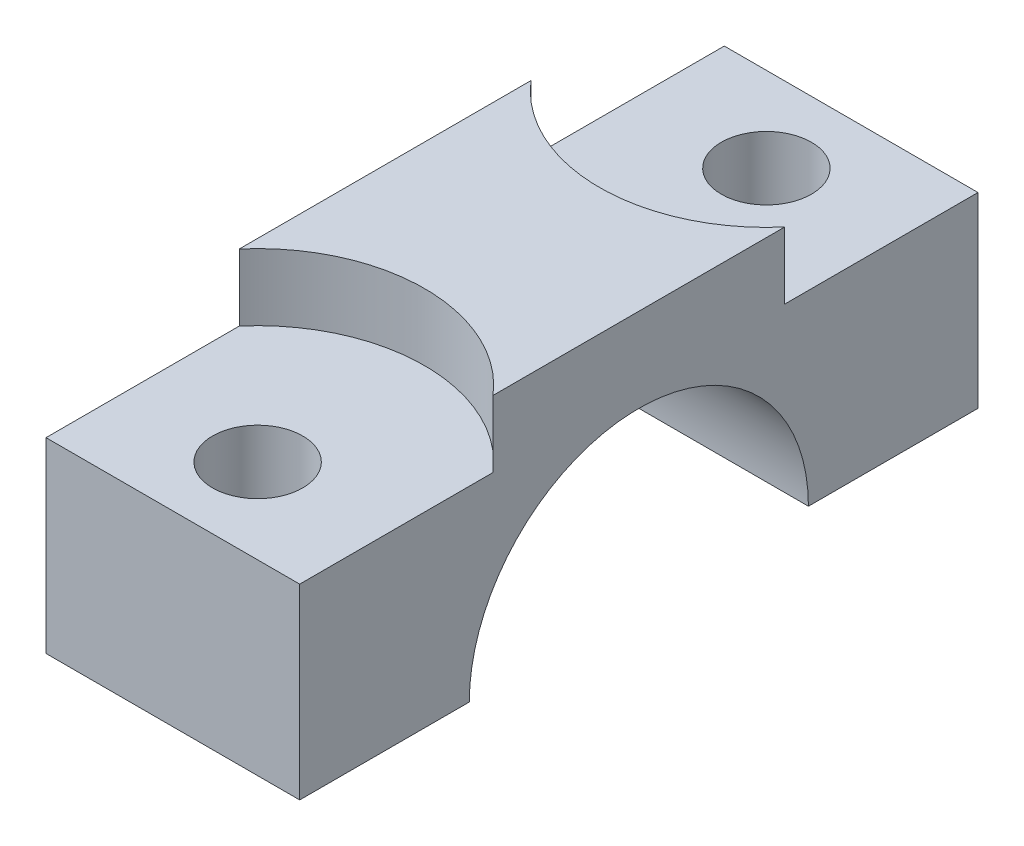
SolidWorks part; units mm, degrees
ref_plane "Front Plane" through (0, 0, 0) normal (0, 0, 1) x (1, 0, 0)
ref_plane "Top Plane" through (0, 0, 0) normal (0, 1, 0) x (1, 0, 0)
ref_plane "Right Plane" through (0, 0, 0) normal (1, 0, 0) x (0, 0, -1)
sketch "Sketch1" plane through (0, 0, 0) normal (1, 0, 0) x (0, 0, -1)
  line L1 (-25.4, 19) -> (25.4, 19)
  line L2 (-25.4, 19) -> (-25.4, 0)
  line L3 (-25.4, 0) -> (25.4, 0)
  line L4 (25.4, 19) -> (25.4, 0)
  circle A0 centre (0, 0) radius 12.7
  dimension "D3" = 25.4
  dimension "D1" = 50.8
  dimension "D2" = 19
extrude "Boss-Extrude1" add sketch "Sketch1" along normal mid plane 19 contours A0 L3 L4 L1 L2
sketch "Sketch2" plane through (0, 0, 0) normal (0, -1, 0) x (1, 0, 0)
  line L0 (0, 25.4) -> (0, 12.7) construction
  line L1 (9.5, 25.4) -> (-9.5, 25.4) construction
  line L2 (9.5, 12.7) -> (-9.5, 12.7) construction
  line L3 (0, -12.7) -> (0, -25.4) construction
  line L4 (9.5, -12.7) -> (-9.5, -12.7) construction
  line L5 (9.5, -25.4) -> (-9.5, -25.4) construction
  point P12 (0, 19.05)
  point P13 (0, -19.05)
sketch "Sketch4" plane through (0, 19, 0) normal (0, 1, 0) x (1, 0, 0)
  point P0 (0, 19.05)
  point P3 (0, -19.05)
hole_wizard "CBORE for M16 Hex Head Cap Screw1" positions "Sketch4" profile "Sketch5" counterbore size "M16" standard "ISO" end condition through all
sketch "Sketch5" plane through (0, 19, -19.05) normal (1, 0, 0) x (0, 0, 1)
  line L0 (0, 0) -> (0, 19)
  line L1 (0, 19) -> (3.375, 19)
  line L3 (3.375, 19) -> (3.375, 5)
  line L4 (3.375, 5) -> (12.5, 5)
  line L5 (12.5, 5) -> (12.5, 0)
  line L7 (12.5, 0) -> (0, 0)
  line L11 (0, -6.35) -> (0, 107.95) construction
  dimension "Thru Hole Dia." = 6.75
  dimension "Thru Hole Depth" = 19
  dimension "C'Bore Dia." = 25
  dimension "C'Bore Depth" = 5
